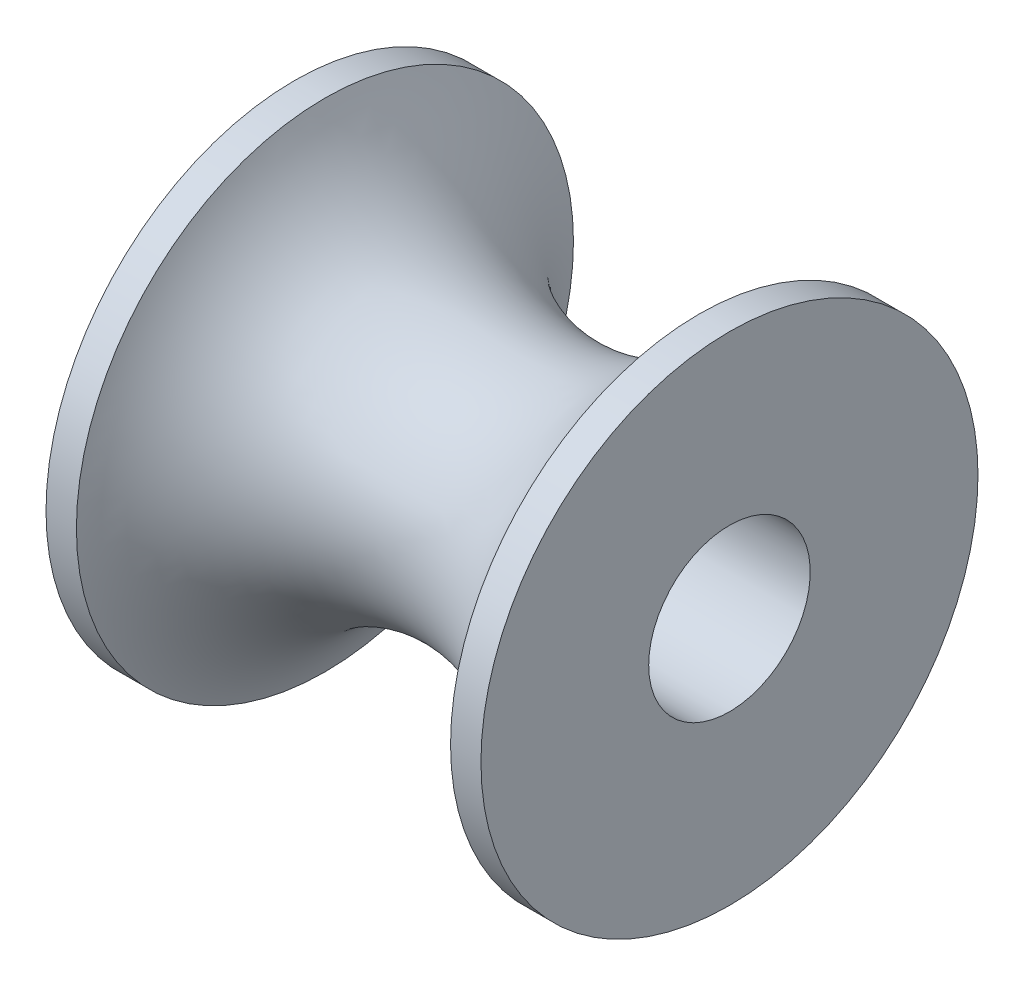
SolidWorks part; units mm, degrees
ref_plane "Front Plane" through (0, 0, 0) normal (0, 0, 1) x (1, 0, 0)
ref_plane "Top Plane" through (0, 0, 0) normal (0, 1, 0) x (1, 0, 0)
ref_plane "Right Plane" through (0, 0, 0) normal (1, 0, 0) x (0, 0, -1)
sketch "Sketch2" plane through (0, 0, 0) normal (0, 1, 0) x (1, 0, 0)
  line L0 (7, 3.9479) -> (7, 10.4479) construction
  line L1 (0, 0) -> (14, 0)
  line L2 (0, 0) -> (0, 8)
  line L3 (0, 8) -> (0.9786, 8)
  line L4 (14, 0) -> (14, 8)
  line L5 (13.0214, 8) -> (14, 8)
  arc A1 (0.9786, 8) -> (13.0214, 8) centre (7, 10.4479) ccw
  circle A2 centre (7, 10.4479) radius 6.5 construction
  dimension "D1" = 13
  dimension "D2" = 14
  dimension "D3" = 8
  dimension "D4" = 6.5
revolve "Revolve2" add sketch "Sketch2" angle 360 about L1
sketch "Sketch3" plane through (0, 0, 0) normal (-1, 0, 0) x (0, 0, 1)
  circle A0 centre (0, 0) radius 2.6
  dimension "D1" = 5.2
extrude "Cut-Extrude1" cut sketch "Sketch3" against normal through all
